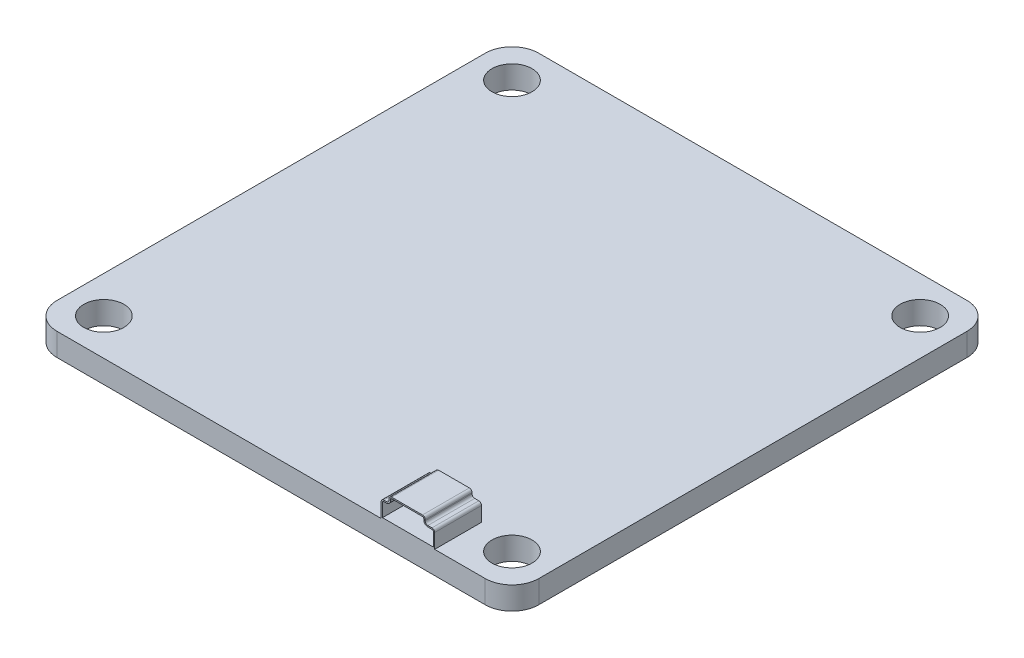
SolidWorks part; units mm, degrees
ref_plane "Front Plane" through (0, 0, 0) normal (0, 0, 1) x (1, 0, 0)
ref_plane "Top Plane" through (0, 0, 0) normal (0, 1, 0) x (1, 0, 0)
ref_plane "Right Plane" through (0, 0, 0) normal (1, 0, 0) x (0, 0, -1)
sketch "Sketch1" plane through (0, 0, 0) normal (0, 1, 0) x (1, 0, 0)
  line L1 (-16, 18) -> (16, 18)
  line L2 (-18, 16) -> (-18, -16)
  line L3 (-16, -18) -> (16, -18)
  line L4 (18, 16) -> (18, -16)
  line L5 (-18, 18) -> (18, -18) construction
  line L6 (-18, -18) -> (18, 18) construction
  line L7 (-15.25, 15.25) -> (15.25, 15.25) construction
  line L8 (-15.25, 15.25) -> (-15.25, -15.25) construction
  line L9 (-15.25, -15.25) -> (15.25, -15.25) construction
  line L10 (15.25, 15.25) -> (15.25, -15.25) construction
  line L11 (-15.25, 15.25) -> (15.25, -15.25) construction
  line L12 (-15.25, -15.25) -> (15.25, 15.25) construction
  circle A0 centre (-15.25, 15.25) radius 1.5
  circle A1 centre (15.25, 15.25) radius 1.5
  circle A2 centre (-15.25, -15.25) radius 1.5
  circle A3 centre (15.25, -15.25) radius 1.5
  arc A4 (-18, -16) -> (-16, -18) centre (-16, -16) ccw
  arc A5 (16, -18) -> (18, -16) centre (16, -16) ccw
  arc A6 (16, 18) -> (18, 16) centre (16, 16) cw
  arc A7 (-16, 18) -> (-18, 16) centre (-16, 16) ccw
  point P0 (0, 0)
  point P6 (0, 0)
  dimension "D4" = 3
  dimension "D5" = 2
  dimension "D1" = 36
  dimension "D2" = 36
  dimension "D3" = 30.5
extrude "Boss-Extrude1" add sketch "Sketch1" along normal blind 1.7
sketch "Sketch2" plane through (0, 0, 18) normal (0, 0, 1) x (1, 0, 0)
  line L0 (-16, 1.7) -> (16, 1.7) construction
  line L1 (8.221, 1.7) -> (12.221, 1.7)
  line L2 (8.221, 1.7) -> (8.221, 2.7913)
  line L3 (9.011, 3.4713) -> (11.311, 3.4713)
  line L4 (12.221, 1.7) -> (12.221, 2.7913)
  line L5 (8.811, 3.2713) -> (8.811, 3.1913)
  line L6 (8.611, 2.9913) -> (8.421, 2.9913)
  line L7 (11.511, 3.2713) -> (11.511, 3.1913)
  line L8 (11.711, 2.9913) -> (12.021, 2.9913)
  line L9 (8.321, 1.8) -> (12.121, 1.8)
  line L10 (12.121, 1.8) -> (12.121, 2.7913)
  line L11 (11.711, 2.8913) -> (12.021, 2.8913)
  line L12 (11.411, 3.2713) -> (11.411, 3.1913)
  line L13 (9.011, 3.3713) -> (11.311, 3.3713)
  line L14 (8.911, 3.2713) -> (8.911, 3.1913)
  line L15 (8.611, 2.8913) -> (8.421, 2.8913)
  line L16 (8.321, 1.8) -> (8.321, 2.7913)
  arc A0 (12.021, 2.9913) -> (12.221, 2.7913) centre (12.021, 2.7913) cw
  arc A1 (11.511, 3.1913) -> (11.711, 2.9913) centre (11.711, 3.1913) ccw
  arc A2 (11.511, 3.2713) -> (11.311, 3.4713) centre (11.311, 3.2713) ccw
  arc A3 (8.811, 3.2713) -> (9.011, 3.4713) centre (9.011, 3.2713) cw
  arc A4 (8.811, 3.1913) -> (8.611, 2.9913) centre (8.611, 3.1913) cw
  arc A5 (8.421, 2.9913) -> (8.221, 2.7913) centre (8.421, 2.7913) ccw
  arc A6 (12.021, 2.8913) -> (12.121, 2.7913) centre (12.021, 2.7913) cw
  arc A7 (11.411, 3.1913) -> (11.711, 2.8913) centre (11.711, 3.1913) ccw
  arc A8 (11.411, 3.2713) -> (11.311, 3.3713) centre (11.311, 3.2713) ccw
  arc A9 (8.911, 3.2713) -> (9.011, 3.3713) centre (9.011, 3.2713) cw
  arc A10 (8.911, 3.1913) -> (8.611, 2.8913) centre (8.611, 3.1913) cw
  arc A11 (8.421, 2.8913) -> (8.321, 2.7913) centre (8.421, 2.7913) ccw
  point P11 (12.221, 2.9913)
  point P15 (11.511, 2.9913)
  point P18 (11.511, 3.4713)
  point P21 (8.811, 3.4713)
  point P24 (8.811, 2.9913)
  point P27 (8.221, 2.9913)
  dimension "D6" = 0.2
  dimension "D1" = 0.71
  dimension "D2" = 0.59
  dimension "D3" = 0.48
  dimension "D4" = 0.48
  dimension "D5" = 4
  dimension "D7" = 0.1
extrude "Boss-Extrude2" add sketch "Sketch2" against normal blind 3
sketch "Sketch3" plane through (0, 0, 15) normal (0, 0, -1) x (-1, 0, 0)
  line L8 (-8.221, 1.7) -> (-8.221, 2.7913)
  line L9 (-8.421, 2.9913) -> (-8.611, 2.9913)
  line L10 (-8.811, 3.1913) -> (-8.811, 3.2713)
  line L11 (-9.011, 3.4713) -> (-11.311, 3.4713)
  line L12 (-11.511, 3.2713) -> (-11.511, 3.1913)
  line L13 (-11.711, 2.9913) -> (-12.021, 2.9913)
  line L14 (-12.221, 2.7913) -> (-12.221, 1.7)
  line L15 (-12.221, 1.7) -> (-8.221, 1.7)
  line L16 (-8.221, 1.7) -> (-8.221, 2.7913)
  line L17 (-8.421, 2.9913) -> (-8.611, 2.9913)
  line L18 (-8.811, 3.1913) -> (-8.811, 3.2713)
  line L19 (-9.011, 3.4713) -> (-11.311, 3.4713)
  line L20 (-11.511, 3.2713) -> (-11.511, 3.1913)
  line L21 (-11.711, 2.9913) -> (-12.021, 2.9913)
  line L22 (-12.221, 2.7913) -> (-12.221, 1.7)
  line L23 (-12.221, 1.7) -> (-8.221, 1.7)
  arc A6 (-8.221, 2.7913) -> (-8.421, 2.9913) centre (-8.421, 2.7913) ccw
  arc A7 (-8.811, 3.1913) -> (-8.611, 2.9913) centre (-8.611, 3.1913) ccw
  arc A8 (-8.811, 3.2713) -> (-9.011, 3.4713) centre (-9.011, 3.2713) ccw
  arc A9 (-11.311, 3.4713) -> (-11.511, 3.2713) centre (-11.311, 3.2713) ccw
  arc A10 (-11.711, 2.9913) -> (-11.511, 3.1913) centre (-11.711, 3.1913) ccw
  arc A11 (-12.021, 2.9913) -> (-12.221, 2.7913) centre (-12.021, 2.7913) ccw
  arc A12 (-8.221, 2.7913) -> (-8.421, 2.9913) centre (-8.421, 2.7913) ccw
  arc A13 (-8.811, 3.1913) -> (-8.611, 2.9913) centre (-8.611, 3.1913) ccw
  arc A14 (-8.811, 3.2713) -> (-9.011, 3.4713) centre (-9.011, 3.2713) ccw
  arc A15 (-11.311, 3.4713) -> (-11.511, 3.2713) centre (-11.311, 3.2713) ccw
  arc A16 (-11.711, 2.9913) -> (-11.511, 3.1913) centre (-11.711, 3.1913) ccw
  arc A17 (-12.021, 2.9913) -> (-12.221, 2.7913) centre (-12.021, 2.7913) ccw
  dimension "D1" = 0
extrude "Boss-Extrude3" add sketch "Sketch3" along normal blind 0.5
sketch "Sketch4" plane through (0, 0, 14.5) normal (0, 0, -1) x (-1, 0, 0)
  line L0 (-12.221, 2.7913) -> (-12.221, 1.7) construction
  line L1 (-9.011, 3.4713) -> (-11.311, 3.4713) construction
  circle A0 centre (-11.121, 2.6713) radius 0.2304
  circle A1 centre (-10.421, 2.6713) radius 0.2304
  circle A2 centre (-9.721, 2.6713) radius 0.2304
  dimension "D1" = 0.7
  dimension "D2" = 0.7
  dimension "D3" = 1.1
  dimension "D4" = 0.8
extrude "Cut-Extrude2" cut sketch "Sketch4" against normal up to next
